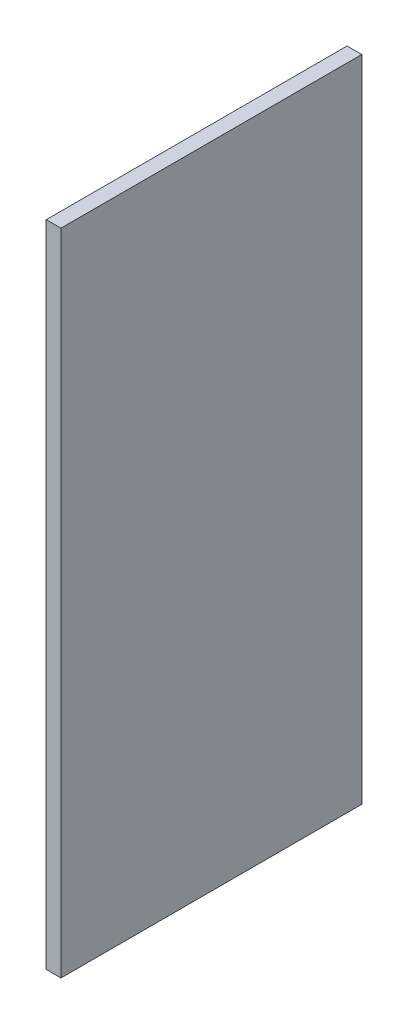
SolidWorks part; units mm, degrees
ref_plane "Front Plane" through (0, 0, 0) normal (0, 0, 1) x (1, 0, 0)
ref_plane "Top Plane" through (0, 0, 0) normal (0, 1, 0) x (1, 0, 0)
ref_plane "Right Plane" through (0, 0, 0) normal (1, 0, 0) x (0, 0, -1)
other "Configuration Table"
sketch "Sketch1" plane through (0, 0, 0) normal (0, 0, 1) x (1, 0, 0)
  line L1 (658.5, 201.5) -> (698.5, 201.5)
  line L2 (658.5, 201.5) -> (658.5, 1968.5)
  line L3 (658.5, 1968.5) -> (698.5, 1968.5)
  line L4 (698.5, 201.5) -> (698.5, 1968.5)
extrude "TOPPING_pu_yan_sag_1" add sketch "Sketch1" against normal blind 818.5 separate body
